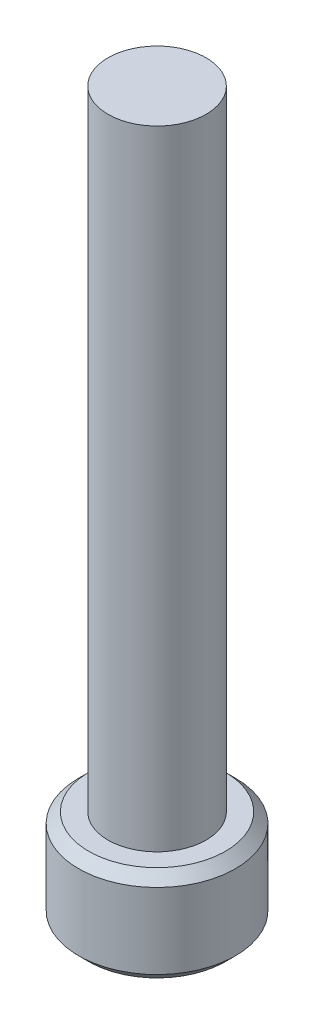
SolidWorks part; units mm, degrees
ref_plane "Front Plane" through (0, 0, 0) normal (0, 0, 1) x (1, 0, 0)
ref_plane "Top Plane" through (0, 0, 0) normal (0, 1, 0) x (1, 0, 0)
ref_plane "Right Plane" through (0, 0, 0) normal (1, 0, 0) x (0, 0, -1)
sketch "Sketch1" plane through (0, 0, 0) normal (0, 1, 0) x (1, 0, 0)
  circle A0 centre (0, 0) radius 2.4765
  dimension "D1" = 4.953
extrude "Boss-Extrude1" add sketch "Sketch1" along normal blind 31.75
sketch "Sketch2" plane through (0, 0, 0) normal (0, -1, 0) x (1, 0, 0)
  circle A0 centre (0, 0) radius 3.9624
  dimension "D1" = 7.9248
extrude "Boss-Extrude2" add sketch "Sketch2" along normal blind 4.826
sketch "Sketch3" plane through (0, -4.826, 0) normal (0, -1, 0) x (1, 0, 0)
  line L1 (2.2914, 0) -> (1.1457, 1.9844)
  line L2 (1.1457, 1.9844) -> (-1.1457, 1.9844)
  line L3 (-1.1457, 1.9844) -> (-2.2914, 0)
  line L4 (-2.2914, 0) -> (-1.1457, -1.9844)
  line L5 (-1.1457, -1.9844) -> (1.1457, -1.9844)
  line L6 (1.1457, -1.9844) -> (2.2914, 0)
  circle A0 centre (0, 0) radius 1.9844 construction
  dimension "D1" = 3.9688
extrude "Cut-Extrude1" cut sketch "Sketch3" against normal blind 2.286
chamfer "Chamfer1" distance 0.508 angle 45 2 edges at (0, -4.826, -3.9624) (0, 0, -3.9624)
